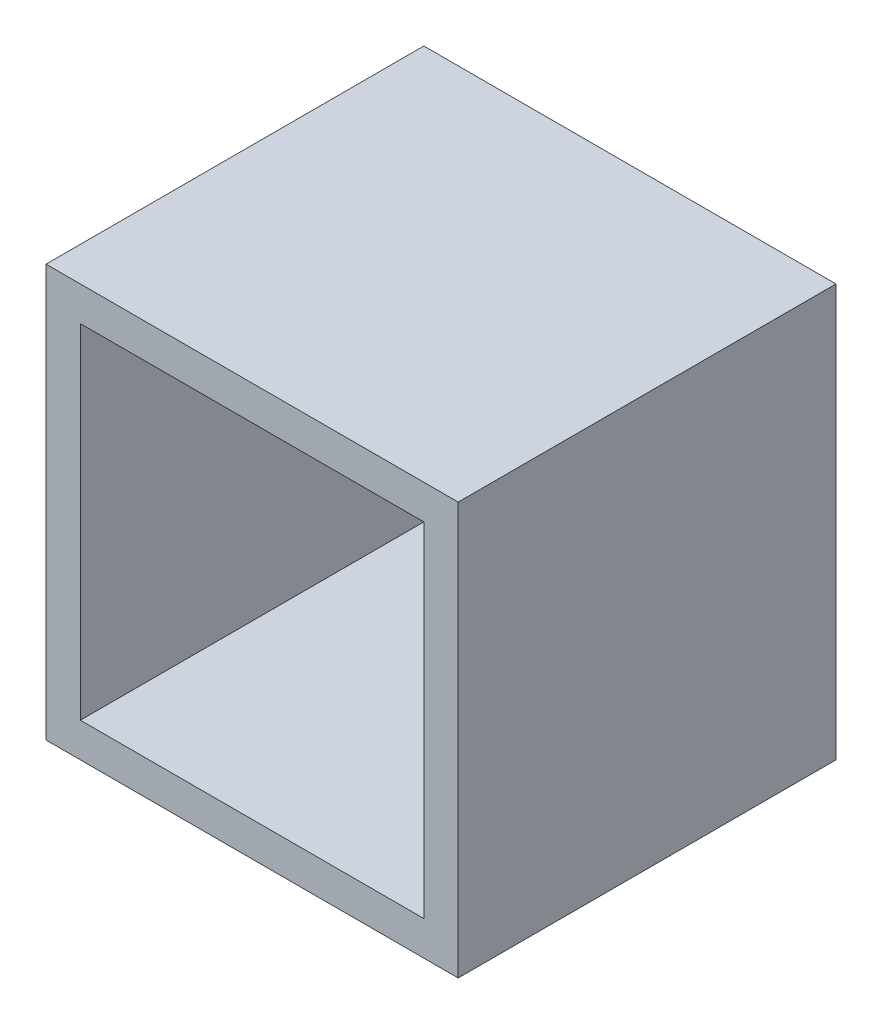
SolidWorks part; units mm, degrees
ref_plane "Front Plane" through (0, 0, 0) normal (0, 0, 1) x (1, 0, 0)
ref_plane "Top Plane" through (0, 0, 0) normal (0, 1, 0) x (1, 0, 0)
ref_plane "Right Plane" through (0, 0, 0) normal (1, 0, 0) x (0, 0, -1)
sketch "Sketch1" plane through (0, 0, 0) normal (0, 0, 1) x (1, 0, 0)
  line L1 (0, 0) -> (5000, 0)
  line L2 (0, 0) -> (0, -5000)
  line L3 (0, -5000) -> (5000, -5000)
  line L4 (5000, 0) -> (5000, -5000)
  dimension "D1" = 5000
  dimension "D2" = 5000
extrude "Boss-Extrude1" add sketch "Sketch1" along normal blind 5000
shell "Shell3" thickness 500
